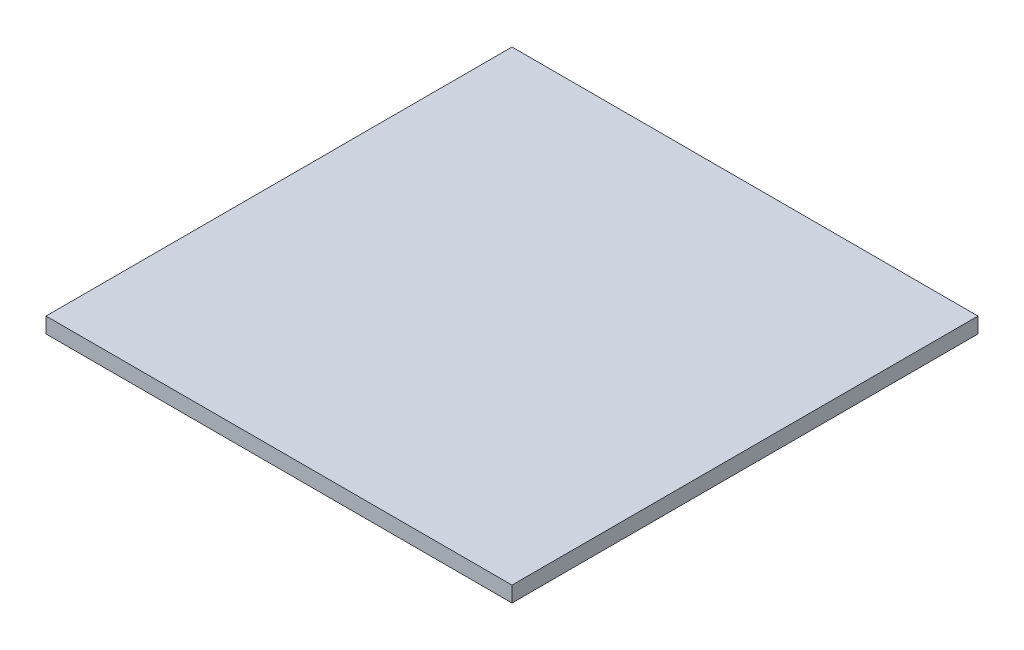
SolidWorks part; units mm, degrees
ref_plane "Front Plane" through (0, 0, 0) normal (0, 0, 1) x (1, 0, 0)
ref_plane "Top Plane" through (0, 0, 0) normal (0, 1, 0) x (1, 0, 0)
ref_plane "Right Plane" through (0, 0, 0) normal (1, 0, 0) x (0, 0, -1)
sketch "Sketch1" plane through (0, 0, 0) normal (0, 1, 0) x (1, 0, 0)
  line L1 (-150, 150) -> (150, 150)
  line L2 (-150, 150) -> (-150, -150)
  line L3 (-150, -150) -> (150, -150)
  line L4 (150, 150) -> (150, -150)
  line L5 (-150, 150) -> (150, -150) construction
  line L6 (-150, -150) -> (150, 150) construction
  point P0 (0, 0)
  dimension "D1" = 300
  dimension "D2" = 300
extrude "Boss-Extrude1" add sketch "Sketch1" along normal blind 10
